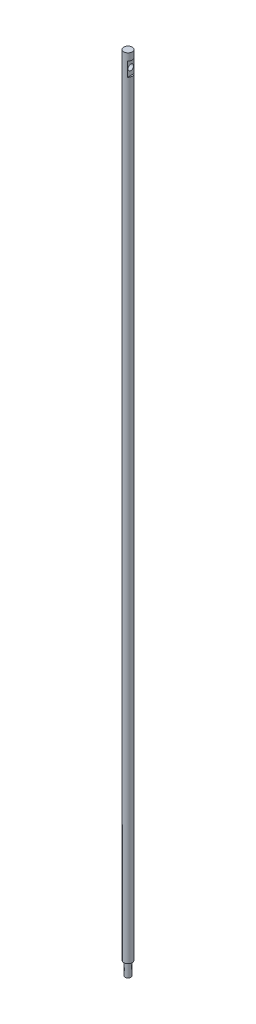
SolidWorks part; units mm, degrees
ref_plane "前视基准面" through (0, 0, 0) normal (0, 0, 1) x (1, 0, 0)
ref_plane "上视基准面" through (0, 0, 0) normal (0, 1, 0) x (1, 0, 0)
ref_plane "右视基准面" through (0, 0, 0) normal (1, 0, 0) x (0, 0, -1)
sketch "草图2" plane through (0, 0, 0) normal (0, 1, 0) x (1, 0, 0)
  circle A0 centre (0, 0) radius 3
  dimension "D1" = 6
extrude "凸台-拉伸1" add sketch "草图2" along normal blind 540
sketch "草图3" plane through (0, 0, 0) normal (0, -1, 0) x (1, 0, 0)
  circle A0 centre (0, 0) radius 2
  dimension "D1" = 4
extrude "凸台-拉伸2" add sketch "草图3" along normal blind 9.5
sketch "草图4" plane through (0, 540, 0) normal (0, 1, 0) x (1, 0, 0)
  line L0 (0, 0) -> (0, 3.3684) construction
  circle A2 centre (0, 0) radius 3
  dimension "D1" = 6
extrude "凸台-拉伸3" add sketch "草图4" along normal blind 20
sketch "草图6" plane through (0, 0, 0) normal (0, 0, 1) x (1, 0, 0)
  line L0 (-3, 555) -> (-3, 545)
  line L1 (-3, 545) -> (-2, 545)
  line L2 (-2, 545) -> (-2, 555)
  line L3 (-2, 555) -> (-3, 555)
  line L4 (0, 560) -> (0, 505.0234) construction
  line L5 (3, 560) -> (-3, 560) construction
  line L6 (3, 545) -> (2, 545)
  line L7 (2, 545) -> (2, 555)
  line L8 (2, 555) -> (3, 555)
  line L9 (3, 555) -> (3, 545)
  dimension "D1" = 1
  dimension "D2" = 10
  dimension "D3" = 6
  dimension "D4" = 5
extrude "切除-拉伸2" cut sketch "草图6" against normal mid plane 10
sketch "草图7" plane through (-2, 0, 0) normal (-1, 0, 0) x (0, 0, 1)
  line L0 (3, 560) -> (-3, 560) construction
  line L1 (0, 560) -> (0, 550) construction
  circle A0 centre (0, 550) radius 2
  dimension "D1" = 4
  dimension "D2" = 10
extrude "切除-拉伸3" cut sketch "草图7" against normal blind 10
